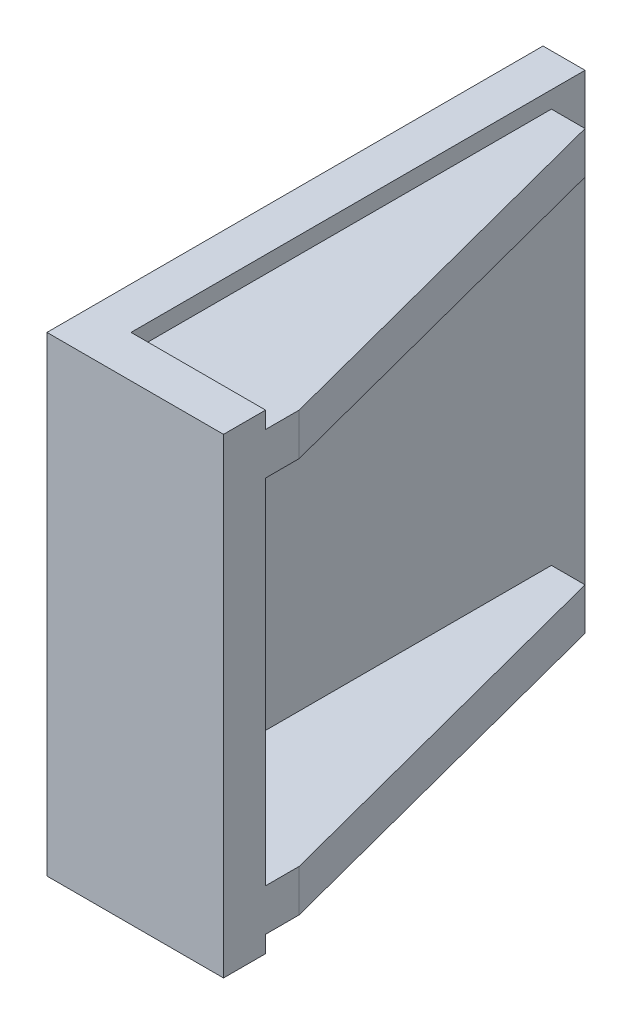
SolidWorks part; units mm, degrees
ref_plane "前视基准面" through (0, 0, 0) normal (0, 0, 1) x (1, 0, 0)
ref_plane "上视基准面" through (0, 0, 0) normal (0, 1, 0) x (1, 0, 0)
ref_plane "右视基准面" through (0, 0, 0) normal (1, 0, 0) x (0, 0, -1)
sketch "草图1" plane through (0, 0, 0) normal (0, 0, 1) x (1, 0, 0)
  line L1 (-12.5, 140) -> (12.5, 140)
  line L2 (-12.5, 140) -> (-12.5, -140)
  line L3 (-12.5, -140) -> (12.5, -140)
  line L4 (12.5, 140) -> (12.5, -140)
  line L5 (-12.5, 140) -> (12.5, -140) construction
  line L6 (-12.5, -140) -> (12.5, 140) construction
  point P0 (0, 0)
  dimension "D1" = 25
  dimension "D2" = 280
extrude "凸台-拉伸1" add sketch "草图1" along normal mid plane 295
sketch "草图2" plane through (0, 140, 0) normal (0, 1, 0) x (1, 0, 0)
  line L1 (12.5, -147.5) -> (92.5, -147.5)
  line L2 (12.5, -147.5) -> (12.5, -122.5)
  line L3 (12.5, -122.5) -> (92.5, -122.5)
  line L4 (92.5, -147.5) -> (92.5, -122.5)
  dimension "D1" = 25
  dimension "D2" = 80
extrude "凸台-拉伸2" add sketch "草图2" against normal up to surface (280 mm away) up to face at (0, -140, 0)
ref_plane "基准面1" through (0, 130, 0) normal (0, 1, 0) x (1, 0, 0)
sketch "草图4" plane through (0, 130, 0) normal (0, 1, 0) x (1, 0, 0)
  line L0 (12.5, 127.5) -> (32.5, 127.5)
  line L1 (12.5, -122.5) -> (12.5, 147.5) construction
  line L2 (32.5, 127.5) -> (92.5, -102.5)
  line L3 (92.5, -102.5) -> (92.5, -122.5)
  line L4 (92.5, -122.5) -> (12.5, -122.5) construction
  line L5 (92.5, -122.5) -> (12.5, -122.5)
  line L6 (12.5, -122.5) -> (12.5, 127.5)
  dimension "D1" = 20
  dimension "D2" = 20
  dimension "D3" = 80
  dimension "D4" = 250
extrude "凸台-拉伸3" add sketch "草图4" against normal blind 25
mirror "镜向1" about plane through (0, 0, 0) normal (0, 1, 0) of "凸台-拉伸3"
equation "\"零件重量\"= \"SW-质量\""
